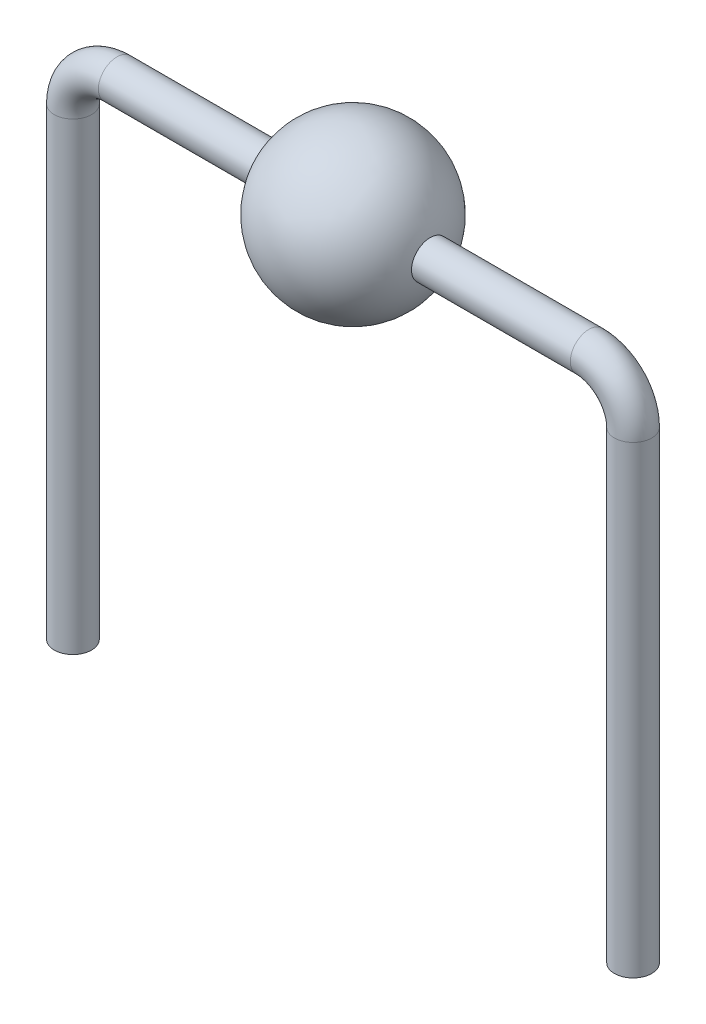
SolidWorks part; units mm, degrees
ref_plane "Спереди" through (0, 0, 0) normal (0, 0, 1) x (1, 0, 0)
ref_plane "Сверху" through (0, 0, 0) normal (0, 1, 0) x (1, 0, 0)
ref_plane "Справа" through (0, 0, 0) normal (1, 0, 0) x (0, 0, -1)
sketch "Эскиз1" plane through (0, 0, 0) normal (0, 1, 0) x (1, 0, 0)
  line L0 (-29.7512, 0) -> (31.712, 0) construction
  line L1 (-1.7496, 0.4231) -> (-1.7496, 0)
  line L2 (-1.7496, 0) -> (1.7496, 0)
  line L3 (0, 2.4294) -> (0, -0.8803) construction
  line L4 (1.7496, 0) -> (1.7496, 0.4231)
  arc A1 (-1.7496, 0.4231) -> (1.7496, 0.4231) centre (0, 0) cw
revolve "Повернуть2" add sketch "Эскиз1" angle 360 about L0
sketch "Эскиз2" plane through (0, 0, 0) normal (0, 0, 1) x (1, 0, 0)
  line L0 (-0.8176, 0) -> (-5.35, 0)
  line L1 (-6.35, -1) -> (-6.35, -11.5149)
  arc A1 (-5.35, 0) -> (-6.35, -1) centre (-5.35, -1) ccw
  dimension "D2" = 6.35
sketch "Эскиз3" plane through (-1.7496, 0, 0) normal (-1, 0, 0) x (0, 0, 1)
  circle A0 centre (0, 0) radius 0.4231
sketch "Эскиз4" plane through (0, 0, 0) normal (0, 0, 1) x (1, 0, 0)
  line L3 (6.35, -11.5149) -> (6.35, -1)
  line L4 (5.35, 0) -> (0.8216, 0)
  arc A0 (6.35, -1) -> (5.35, 0) centre (5.35, -1) ccw
  dimension "D3" = 1
sketch "Эскиз5" plane through (1.7496, 0, 0) normal (1, 0, 0) x (0, 0, -1)
  circle A0 centre (0, 0) radius 0.4231
sweep "По траектории1" add profiles "Эскиз3" path "Эскиз2"
sweep "По траектории2" add profiles "Эскиз5" path "Эскиз4"
